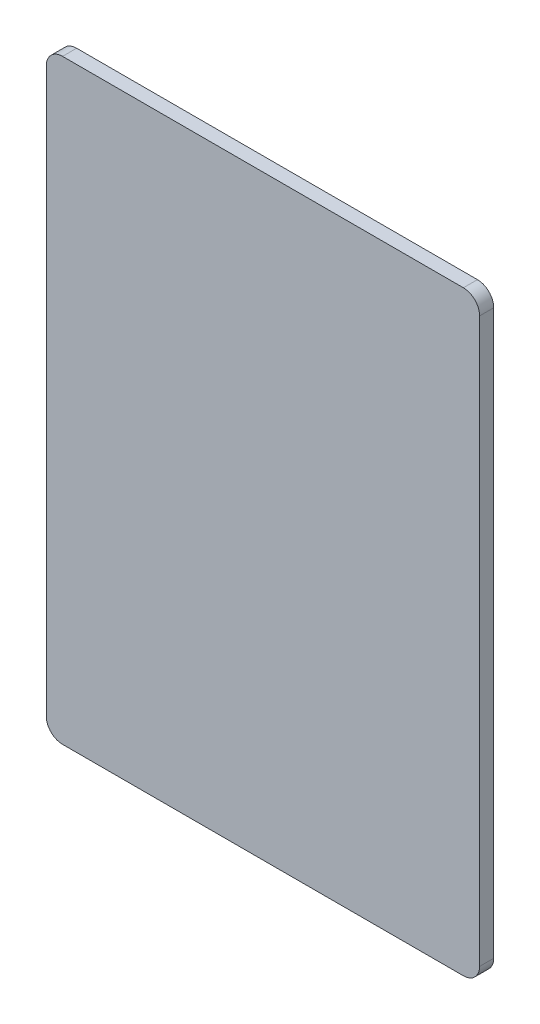
SolidWorks part; units mm, degrees
ref_plane "Front Plane" through (0, 0, 0) normal (1, 0, 0) x (0, 1, 0)
ref_plane "Top Plane" through (0, 0, 0) normal (0, 0, 1) x (0, 1, 0)
ref_plane "Right Plane" through (0, 0, 0) normal (0, 1, 0) x (-1, 0, 0)
sketch "Sketch1" plane through (0, 0, 0) normal (0, 0, 1) x (0, 1, 0)
  line L1 (-27.5, -20) -> (27.5, -20)
  line L2 (-27.5, -20) -> (-27.5, 20)
  line L3 (-27.5, 20) -> (27.5, 20)
  line L4 (27.5, -20) -> (27.5, 20)
  line L5 (-27.5, -20) -> (27.5, 20) construction
  line L6 (-27.5, 20) -> (27.5, -20) construction
  point P0 (0, 0)
  dimension "D1" = 55
  dimension "D2" = 40
extrude "Boss-Extrude1" add sketch "Sketch1" along normal blind 1.3
fillet "Fillet1" radius 1.5 4 edges at (-20, 27.5, 0.65) (-20, -27.5, 0.65) (20, 27.5, 0.65) (20, -27.5, 0.65)
